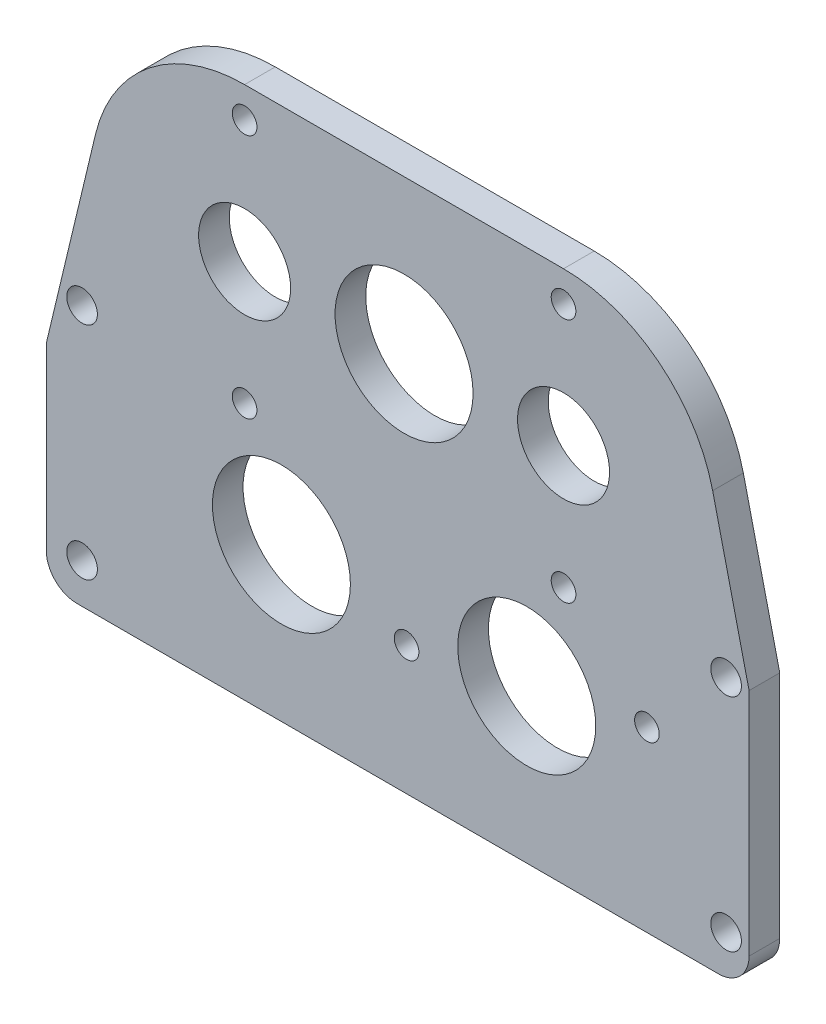
SolidWorks part; units mm, degrees
ref_plane "Front Plane" through (0, 0, 0) normal (0, 0, 1) x (1, 0, 0)
ref_plane "Top Plane" through (0, 0, 0) normal (0, 1, 0) x (1, 0, 0)
ref_plane "Right Plane" through (0, 0, 0) normal (1, 0, 0) x (0, 0, -1)
sketch "Sketch1" plane through (0, 0, 0) normal (0, 0, 1) x (1, 0, 0)
  line L0 (0, 0) -> (-28088.6063, 0) construction
  line L1 (0, 0) -> (0, -28088.6063) construction
  line L2 (1.5394, 46.9041) -> (-37.2217, 46.9041) construction
  line L3 (50.8, 0) -> (50.8, 50000) construction
  line L4 (-7.62, 72.3041) -> (-7.62, 21.5041) construction
  line L5 (58.42, 72.3041) -> (58.42, 21.5041) construction
  line L6 (-110.2422, 31.75) -> (49889.7578, 31.75) construction
  line L7 (-115.6814, -31.75) -> (-48.6893, -31.75) construction
  line L8 (25.9168, -5.0978) -> (75.6832, 5.0978) construction
  line L9 (-110.2422, 28.575) -> (49889.7578, 28.575) construction
  line L10 (-41.275, 22.225) -> (92.075, 22.225) construction
  line L11 (-41.275, 22.225) -> (-41.275, -23.495) construction
  line L12 (92.075, 22.225) -> (92.075, -23.495) construction
  line L13 (-41.275, -23.495) -> (92.075, -23.495) construction
  line L14 (-115.6814, -28.575) -> (-69.348, -28.575) construction
  line L15 (-48.6893, -31.75) -> (96.8375, -31.75)
  line L16 (-38.4982, 54.2931) -> (-48.6893, 11.7053)
  line L17 (-48.6893, 11.7053) -> (-48.6893, -31.75)
  line L18 (96.8375, 22.225) -> (96.8375, -31.75)
  line L20 (-7.62, 78.6541) -> (58.42, 78.6541)
  line L21 (96.8375, 22.225) -> (89.2982, 54.2931)
  line L22 (-115.6814, -31.75) -> (49884.3186, -31.75) construction
  line L24 (-115.6814, -28.575) -> (49884.3186, -28.575) construction
  line L25 (-48.6893, -31.75) -> (96.8375, -31.75) construction
  circle A0 centre (0, 0) radius 14.2875
  circle A1 centre (50.8, 0) radius 14.2875
  circle A2 centre (25.4, 46.9041) radius 14.2875
  circle A3 centre (0, 0) radius 34.29 construction
  circle A4 centre (50.8, 0) radius 16.51 construction
  circle A5 centre (50.8, 0) radius 38.1 construction
  circle A6 centre (25.4, 46.9041) radius 25.4 construction
  circle A7 centre (-7.62, 46.9041) radius 7.62 construction
  circle A8 centre (58.42, 46.9041) radius 7.62 construction
  circle A9 centre (-7.62, 72.3041) radius 2.5527
  circle A10 centre (-7.62, 21.5041) radius 2.5527
  circle A11 centre (58.42, 72.3041) radius 2.5527
  circle A12 centre (58.42, 21.5041) radius 2.5527
  circle A13 centre (-7.62, 46.9041) radius 31.75 construction
  circle A14 centre (58.42, 46.9041) radius 31.75 construction
  circle A15 centre (58.42, 46.9041) radius 9.525
  circle A16 centre (-7.62, 46.9041) radius 9.525
  circle A17 centre (75.6832, 5.0978) radius 2.5527
  circle A18 centre (25.9168, -5.0978) radius 2.5527
  circle A19 centre (-41.275, 22.225) radius 3.175
  circle A20 centre (92.075, 22.225) radius 3.175
  circle A21 centre (-41.275, -23.495) radius 3.175
  circle A22 centre (92.075, -23.495) radius 3.175
  circle A23 centre (92.075, 22.225) radius 4.7625 construction
  circle A24 centre (50.8, 0) radius 39.37 construction
  circle A25 centre (-41.275, 22.225) radius 4.7625 construction
  circle A26 centre (-41.275, -23.495) radius 4.7625 construction
  circle A27 centre (92.075, -23.495) radius 4.7625 construction
  arc A28 (58.42, 78.6541) -> (89.2982, 54.2931) centre (58.42, 46.9041) cw
  arc A29 (-38.4982, 54.2931) -> (-7.62, 78.6541) centre (-7.62, 46.9041) cw
  circle A30 centre (25.4, 46.9041) radius 15.24 construction
  dimension "D1" = 28.575
  dimension "D2" = 68.58
  dimension "D3" = 33.02
  dimension "D4" = 76.2
  dimension "D5" = 50.8
  dimension "D6" = 15.24
  dimension "D10" = 5.1054
  dimension "D11" = 63.5
  dimension "D12" = 19.05
  dimension "D16" = 5.1054
  dimension "D18" = 6.35
  dimension "D25" = 9.525
  dimension "D26" = 78.74
  dimension "D27" = 30.48
  dimension "D7" = 25.4
  dimension "D8" = 50.8
  dimension "D9" = 25.4
  dimension "D13" = 31.75
  dimension "D14" = 31.75
  dimension "D15" = 50.8
  dimension "D17" = 5.0978
  dimension "D21" = 41.275
  dimension "D22" = 6.35
  dimension "D20" = 41.275
  dimension "D24" = 5.08
  dimension "D19" = 3.175
  dimension "D23" = 3.175
extrude "Boss-Extrude2" add sketch "Sketch1" along normal blind 6.35
fillet "Fillet1" radius 6.35 2 edges at (96.8375, -31.75, 3.175) (-48.6893, -31.75, 3.175)
equation "\"D2@Sketch1\"=54/20"
equation "\"D3@Sketch1\"=26/20"
equation "\"D4@Sketch1\"=60/20"
equation "\"D5@Sketch1\"=40/20"
equation "\"D6@Sketch1\"=12/20"
equation "\"D9@Sketch1\"=\"D8@Sketch1\"/2"
equation "\"D13@Sketch1\"=2.5/2"
equation "\"D14@Sketch1\"=2.5/2"
equation "\"D20@Sketch1\"=\"D21@Sketch1\""
equation "\"D25@Sketch1\"=3/8"
